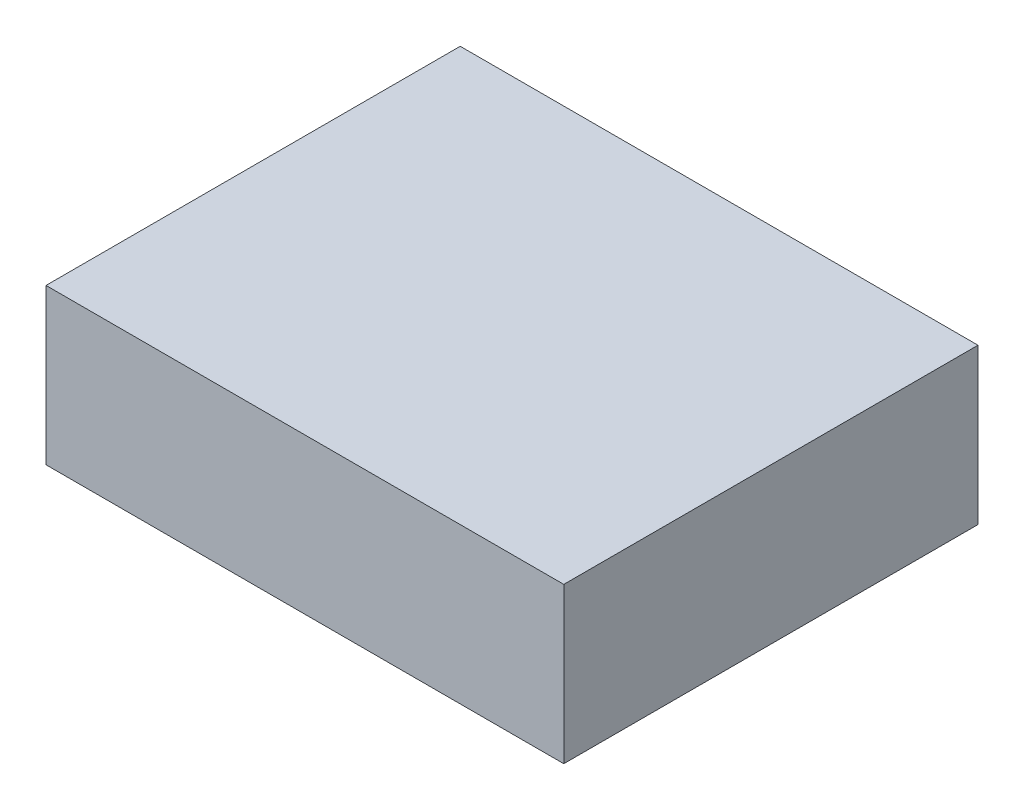
SolidWorks part; units mm, degrees
ref_plane "Front Plane" through (0, 0, 0) normal (0, 0, 1) x (1, 0, 0)
ref_plane "Top Plane" through (0, 0, 0) normal (0, 1, 0) x (1, 0, 0)
ref_plane "Right Plane" through (0, 0, 0) normal (1, 0, 0) x (0, 0, -1)
sketch "Sketch1" plane through (0, 0, 0) normal (0, 1, 0) x (1, 0, 0)
  line L1 (-50, 40) -> (50, 40)
  line L2 (-50, 40) -> (-50, -40)
  line L3 (-50, -40) -> (50, -40)
  line L4 (50, 40) -> (50, -40)
  line L5 (-50, 40) -> (50, -40) construction
  line L6 (-50, -40) -> (50, 40) construction
  point P4 (0, 0)
  point P5 (0, 0)
  dimension "D1" = 100
  dimension "D2" = 80
extrude "Boss-Extrude1" add sketch "Sketch1" along normal blind 30
